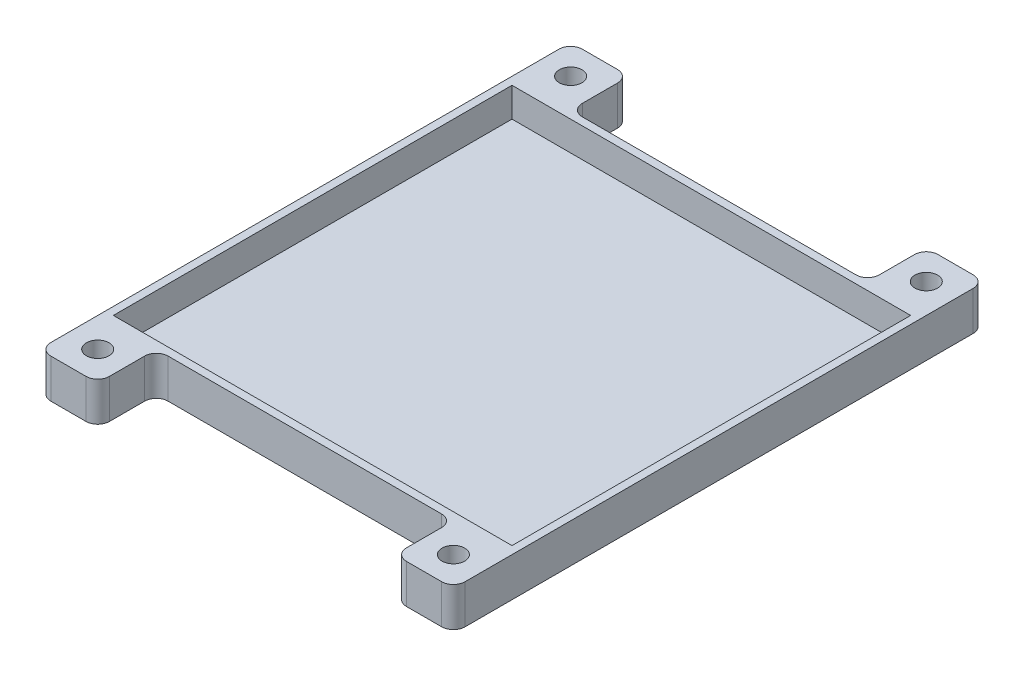
SolidWorks part; units mm, degrees
material "PVC 0.007 Plasticized"
ref_plane "Front Plane" through (0, 0, 0) normal (0, 0, 1) x (1, 0, 0)
ref_plane "Top Plane" through (0, 0, 0) normal (0, 1, 0) x (1, 0, 0)
ref_plane "Right Plane" through (0, 0, 0) normal (1, 0, 0) x (0, 0, -1)
sketch "Sketch1" plane through (0, 0, 0) normal (0, 1, 0) x (1, 0, 0)
  line L1 (-53, -53) -> (53, -53)
  line L2 (-53, -53) -> (-53, 53)
  line L3 (-53, 53) -> (53, 53)
  line L4 (53, -53) -> (53, 53)
  line L5 (-53, -53) -> (53, 53) construction
  line L6 (-53, 53) -> (53, -53) construction
  point P0 (0, 0)
  dimension "D1" = 106
  dimension "D2" = 106
extrude "Boss-Extrude1" add sketch "Sketch1" against normal blind 8.5
shell "Shell1" thickness 2
sketch "Sketch2" plane through (0, -6.5, 0) normal (0, 1, 0) x (1, 0, 0)
  line L0 (0, 53) -> (0, -53) construction
  line L13 (-38, 68) -> (-53, 68)
  line L14 (-38, 68) -> (-38, 53)
  line L15 (-38, 53) -> (-53, 53)
  line L16 (-53, 68) -> (-53, 53)
  line L17 (53, 53) -> (-53, 53) construction
  line L18 (-53, -53) -> (53, -53) construction
  line L19 (-53, 0) -> (53, 0) construction
  line L20 (-53, 53) -> (-53, -53) construction
  line L21 (53, -53) -> (53, 53) construction
  line L22 (38, 53) -> (53, 53)
  line L23 (53, 68) -> (53, 53)
  line L24 (38, 68) -> (53, 68)
  line L25 (38, 68) -> (38, 53)
  line L26 (38, -68) -> (38, -53)
  line L27 (38, -68) -> (53, -68)
  line L28 (53, -68) -> (53, -53)
  line L29 (38, -53) -> (53, -53)
  line L30 (-38, -53) -> (-53, -53)
  line L31 (-53, -68) -> (-53, -53)
  line L32 (-38, -68) -> (-53, -68)
  line L33 (-38, -68) -> (-38, -53)
  dimension "D1" = 15
  dimension "D2" = 15
extrude "Boss-Extrude2" add sketch "Sketch2" along normal up to surface and the other way up to surface
sketch "Sketch3" plane through (0, 0, 0) normal (0, 1, 0) x (1, 0, 0)
  line L4 (-38, 68) -> (-53, 68) construction
  line L5 (-45.5, 68) -> (-45.5, 37) construction
  line L7 (0, -55) -> (0, 55) construction
  line L8 (45.5, 68) -> (45.5, 37) construction
  line L9 (38, 68) -> (53, 68) construction
  line L11 (38, 53) -> (38, 68) construction
  line L12 (-55, 0) -> (55, 0) construction
  line L13 (38, -53) -> (38, -68) construction
  line L15 (38, -68) -> (53, -68) construction
  line L16 (45.5, -68) -> (45.5, -37) construction
  line L17 (-45.5, -68) -> (-45.5, -37) construction
  line L18 (-38, -68) -> (-53, -68) construction
  line L21 (-53, 68) -> (-38, 68) construction
  line L23 (-38, 53) -> (-53, 53) construction
  line L24 (-53, 68) -> (-53, -68) construction
  line L25 (-38, 68) -> (-38, 53) construction
  circle A0 centre (-45.5, 60.5) radius 7.5 construction
  circle A1 centre (45.5, 60.5) radius 7.5 construction
  circle A2 centre (45.5, -60.5) radius 7.5 construction
  circle A3 centre (-45.5, -60.5) radius 7.5 construction
  point P15 (-45.5, 60.5)
  point P19 (45.5, 60.5)
  point P30 (45.5, -60.5)
  point P32 (-45.5, -60.5)
  point P54 (-45.5, 68)
  point P72 (-38, 60.5)
  dimension "D1" = 7.5
hole_wizard "M5 Clearance Hole1" positions "Sketch3" profile "Sketch4" hole size "M5" standard "ANSI Metric" end condition through all
sketch "Sketch4" plane through (-45.5, 0, 60.5) normal (1, 0, 0) x (0, 0, 1)
  line L0 (0, 0) -> (0, 8.5)
  line L1 (0, 8.5) -> (2.9, 8.5)
  line L2 (2.9, 8.5) -> (2.9, 0)
  line L5 (2.9, 0) -> (0, 0)
  line L11 (0, -6.35) -> (0, 107.95) construction
  dimension "Thru Hole Dia." = 5.8
  dimension "Thru Hole Depth" = 8.5
sketch "Sketch5" plane through (0, 0, 0) normal (0, 1, 0) x (1, 0, 0)
  line L4 (51, -51) -> (51, 51)
  line L5 (51, 51) -> (-51, 51)
  line L6 (-51, 51) -> (-51, -51)
  line L7 (-51, -51) -> (51, -51)
  line L8 (51, -51) -> (51, 51)
  line L9 (51, 51) -> (-51, 51)
  line L10 (-51, 51) -> (-51, -51)
  line L11 (-51, -51) -> (51, -51)
  line L12 (53, -68) -> (53, 68)
  line L17 (53, -68) -> (53, 68)
  line L20 (-38, -53) -> (38, -53)
  line L26 (38, 53) -> (-38, 53)
  line L32 (-38, -53) -> (38, -53)
  line L38 (38, 53) -> (-38, 53)
  line L52 (-53, 68) -> (-53, -68)
  line L54 (-53, 68) -> (-53, -68)
  line L56 (53, 68) -> (38, 68)
  line L58 (53, 68) -> (38, 68)
  line L60 (38, 68) -> (38, 53)
  line L62 (38, 68) -> (38, 53)
  line L64 (-38, 53) -> (-38, 68)
  line L65 (-38, 53) -> (-38, 68)
  line L66 (-38, 68) -> (-53, 68)
  line L67 (-38, 68) -> (-53, 68)
  line L68 (-53, -68) -> (-38, -68)
  line L69 (-53, -68) -> (-38, -68)
  line L70 (-38, -68) -> (-38, -53)
  line L71 (-38, -68) -> (-38, -53)
  line L72 (38, -53) -> (38, -68)
  line L73 (38, -53) -> (38, -68)
  line L74 (38, -68) -> (53, -68)
  line L75 (38, -68) -> (53, -68)
  circle A0 centre (45.5, -60.5) radius 2.9 construction
  circle A1 centre (45.5, 60.5) radius 2.9 construction
  circle A2 centre (-45.5, 60.5) radius 2.9 construction
  circle A3 centre (-45.5, -60.5) radius 2.9 construction
  circle A4 centre (45.5, -60.5) radius 2.9
  circle A5 centre (45.5, 60.5) radius 2.9
  circle A6 centre (-45.5, 60.5) radius 2.9
  circle A7 centre (-45.5, -60.5) radius 2.9
  dimension "D1" = 0
  dimension "D2" = 0
extrude "Boss-Extrude3" add sketch "Sketch5" along normal blind 1.5 contours L32 L73 L75 L17 L58 L62 L38 L65 L67 L54 L69 L71 | L8 L9 L10 L11 | A7 | A6 | A5 | A4
fillet "Fillet2" radius 3 12 edges at (-53, -3.5, -68) (53, -3.5, 68) (-38, -3.5, 68) (-53, -3.5, 68) (-38, -3.5, -68) (-38, -3.5, -53) (38, -3.5, -53) (38, -3.5, -68) (53, -3.5, -68) (38, -3.5, 68) (38, -3.5, 53) (-38, -3.5, 53)
sketch "Sketch6" plane through (0, -6.5, 0) normal (0, 1, 0) x (1, 0, 0)
  line L4 (51, -51) -> (51, 51)
  line L5 (51, 51) -> (-51, 51)
  line L6 (-51, 51) -> (-51, -51)
  line L7 (-51, -51) -> (51, -51)
  line L8 (51, -51) -> (51, 51)
  line L9 (51, 51) -> (-51, 51)
  line L10 (-51, 51) -> (-51, -51)
  line L11 (-51, -51) -> (51, -51)
  dimension "D1" = 0
extrude "Boss-Extrude4" add sketch "Sketch6" along normal offset from surface (0.5 mm away) 7.5 up to face at (0, 1.5, 0)
